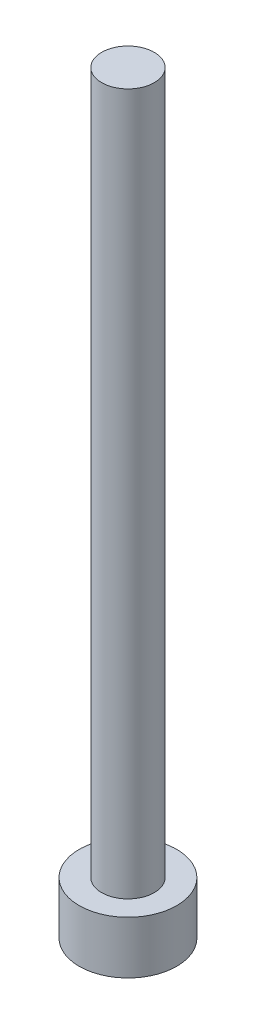
SolidWorks part; units mm, degrees
ref_plane "Front Plane" through (0, 0, 0) normal (0, 0, 1) x (1, 0, 0)
ref_plane "Top Plane" through (0, 0, 0) normal (0, 1, 0) x (1, 0, 0)
ref_plane "Right Plane" through (0, 0, 0) normal (1, 0, 0) x (0, 0, -1)
sketch "Sketch1" plane through (0, 0, 0) normal (0, 1, 0) x (1, 0, 0)
  circle A0 centre (0, 0) radius 2.78
  dimension "D1" = 5.56
extrude "Boss-Extrude1" add sketch "Sketch1" along normal blind 3
sketch "Sketch2" plane through (0, 3, 0) normal (0, 1, 0) x (1, 0, 0)
  circle A0 centre (0, 0) radius 1.5
  dimension "D1" = 3
extrude "Boss-Extrude2" add sketch "Sketch2" along normal blind 40
